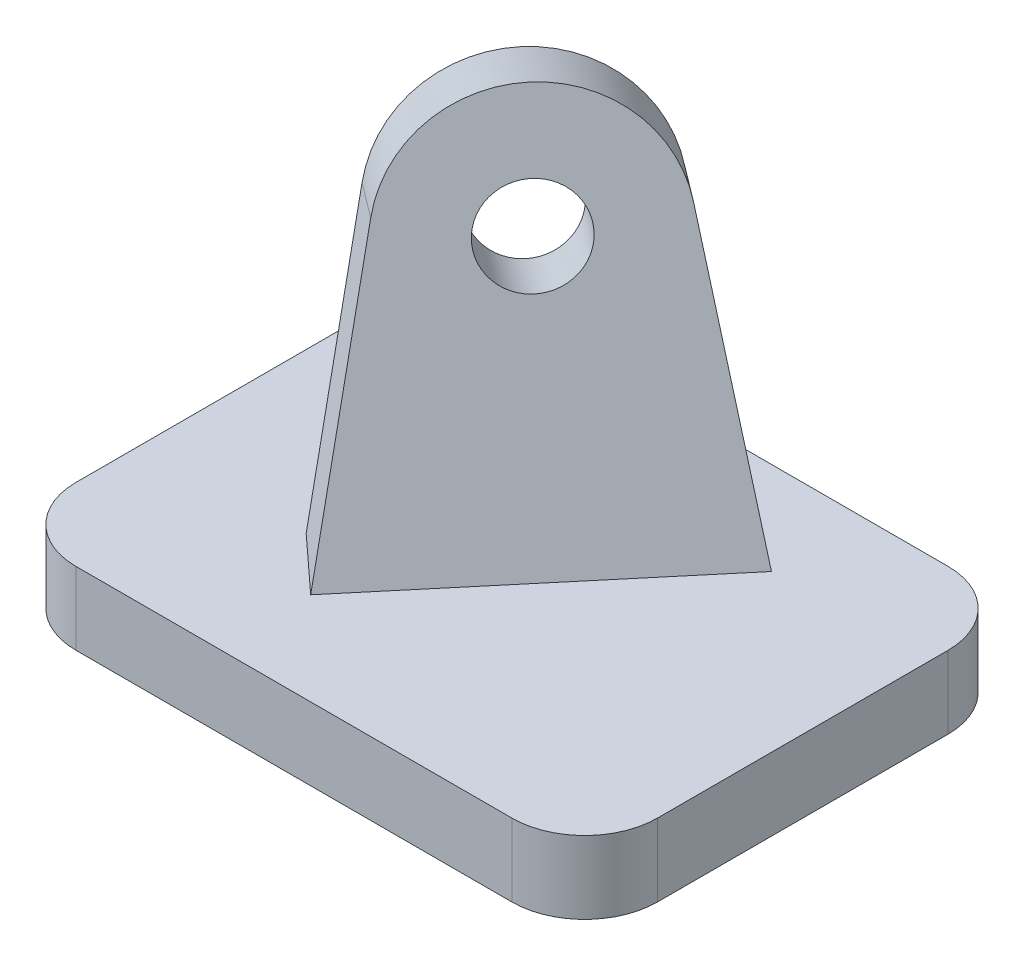
SolidWorks part; units mm, degrees
ref_plane "前视基准面" through (0, 0, 0) normal (0, 0, 1) x (1, 0, 0)
ref_plane "上视基准面" through (0, 0, 0) normal (0, 1, 0) x (1, 0, 0)
ref_plane "右视基准面" through (0, 0, 0) normal (1, 0, 0) x (0, 0, -1)
other "Configuration Table"
sketch "草图1" plane through (0, 0, 0) normal (0, 1, 0) x (1, 0, 0)
  line L1 (-30, 30) -> (30, 30)
  line L2 (-40, 20) -> (-40, -20)
  line L3 (-30, -30) -> (30, -30)
  line L4 (40, 20) -> (40, -20)
  line L5 (-40, 30) -> (40, -30) construction
  line L6 (-40, -30) -> (40, 30) construction
  arc A0 (30, 30) -> (40, 20) centre (30, 20) cw
  arc A1 (-40, -20) -> (-30, -30) centre (-30, -20) ccw
  arc A2 (-30, 30) -> (-40, 20) centre (-30, 20) ccw
  arc A3 (30, -30) -> (40, -20) centre (30, -20) ccw
  point P0 (0, 0)
  dimension "D3" = 10
  dimension "D1" = 60
  dimension "D2" = 80
extrude "凸台-拉伸1" add sketch "草图1" along normal blind 10
sketch "草图4" plane through (0, 10, 0) normal (0, 1, 0) x (1, 0, 0)
  line L0 (4, 31.6852) -> (4, -32.5362) construction
  line L1 (40, -20) -> (40, 20) construction
  line L2 (-40, 20) -> (-40, -20) construction
  line L3 (-40, 0) -> (4, 0) construction
  line L4 (-10.4627, -17.236) -> (18.4627, 17.236)
  line L5 (-30, -30) -> (30, -30) construction
  point P12 (4, 0)
  dimension "D1" = 36
  dimension "D2" = 50
ref_plane "基准面2" through (4.1052, 1.4359, 3.4446) normal (0.7399, 0.2588, 0.6209) x (0.6428, 0, -0.766)
sketch "草图5" plane through (4.1052, 1.4359, 3.4446) normal (0.7399, 0.2588, 0.6209) x (0.6428, 0, -0.766)
  line L0 (-19.9288, 8.8662) -> (25.0712, 8.8662) construction
  line L1 (-19.9288, 8.8662) -> (25.0712, 8.8662)
  line L2 (2.5712, 29.9845) -> (2.5712, 6.5197) construction
  line L3 (-19.9288, 8.8662) -> (-13.1923, 47.6072)
  line L4 (25.0712, 8.8662) -> (18.3346, 47.6072)
  circle A0 centre (2.5712, 44.8662) radius 6
  arc A2 (-13.1923, 47.6072) -> (18.3346, 47.6072) centre (2.5712, 44.8662) cw
  dimension "D2" = 12
  dimension "D3" = 16
  dimension "D1" = 36
extrude "凸台-拉伸2" add sketch "草图5" against normal blind 10
